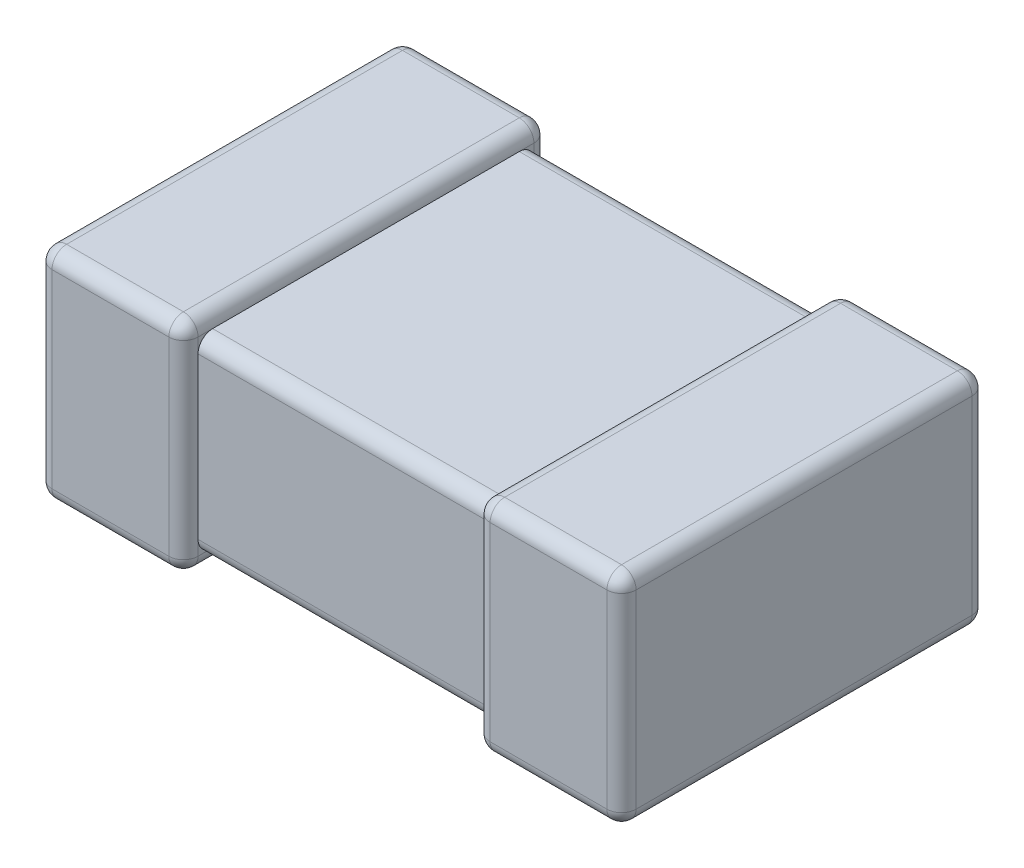
SolidWorks part; units mm, degrees
ref_plane "Front Plane" through (0, 0, 0) normal (0, 0, 1) x (1, 0, 0)
ref_plane "Top Plane" through (0, 0, 0) normal (0, 1, 0) x (1, 0, 0)
ref_plane "Right Plane" through (0, 0, 0) normal (1, 0, 0) x (0, 0, -1)
ref_plane "Plane4" through (0, 0.05, 0) normal (0, 1, 0) x (1, 0, 0)
sketch "Sketch1" plane through (0, 0.05, 0) normal (0, 1, 0) x (1, 0, 0)
  line L1 (-0.95, 0.575) -> (0.95, 0.575)
  line L2 (-0.95, 0.575) -> (-0.95, -0.575)
  line L3 (-0.95, -0.575) -> (0.95, -0.575)
  line L4 (0.95, 0.575) -> (0.95, -0.575)
  dimension "D1" = 1.9
  dimension "D2" = 0.95
  dimension "D3" = 1.15
  dimension "D4" = 0.575
extrude "Boss-Extrude1" add sketch "Sketch1" along normal blind 0.65
sketch "Sketch2" plane through (0, 0, 0) normal (0, 1, 0) x (1, 0, 0)
  line L0 (-0.95, 0.575) -> (-0.95, -0.575) construction
  line L1 (-1, 0.625) -> (-0.5, 0.625)
  line L2 (-1, 0.625) -> (-1, -0.625)
  line L3 (-1, -0.625) -> (-0.5, -0.625)
  line L4 (-0.5, 0.625) -> (-0.5, -0.625)
  line L5 (0.5, 0.625) -> (1, 0.625)
  line L6 (0.5, 0.625) -> (0.5, -0.625)
  line L7 (0.5, -0.625) -> (1, -0.625)
  line L8 (1, 0.625) -> (1, -0.625)
  line L9 (0.95, -0.575) -> (0.95, 0.575) construction
  line L10 (-0.95, -0.575) -> (0.95, -0.575) construction
  line L11 (0.95, 0.575) -> (-0.95, 0.575) construction
  dimension "D1" = 0.05
  dimension "D2" = 0.05
  dimension "D3" = 0.5
  dimension "D4" = 0.5
  dimension "D5" = 0.05
  dimension "D6" = 0.05
extrude "Boss-Extrude2" add sketch "Sketch2" along normal offset from surface (0.75 mm away) 0.05 separate body up to face at (0, 0.7, 0) offset beyond the face yes
fillet "Fillet1" radius 0.05 12 edges at (0.5, 0, 0) (0.75, 0, 0.625) (0.5, 0.375, 0.625) (1, 0, 0) (1, 0.375, 0.625) (0.5, 0.375, -0.625) (0.75, 0, -0.625) (1, 0.375, -0.625) (1, 0.75, 0) (0.75, 0.75, 0.625) (0.5, 0.75, 0) (0.75, 0.75, -0.625)
fillet "Fillet2" radius 0.05 12 edges at (-0.5, 0.375, -0.625) (-0.5, 0, 0) (-0.75, 0, -0.625) (-1, 0, 0) (-1, 0.375, -0.625) (-0.5, 0.375, 0.625) (-0.75, 0, 0.625) (-1, 0.375, 0.625) (-0.5, 0.75, 0) (-0.75, 0.75, 0.625) (-1, 0.75, 0) (-0.75, 0.75, -0.625)
fillet "Fillet3" radius 0.05 12 edges at (0.95, 0.05, 0) (-0.95, 0.05, 0) (0.95, 0.375, -0.575) (-0.95, 0.375, -0.575) (0, 0.05, -0.575) (-0.95, 0.375, 0.575) (0.95, 0.375, 0.575) (0, 0.05, 0.575) (0, 0.7, -0.575) (0.95, 0.7, 0) (0, 0.7, 0.575) (-0.95, 0.7, 0)
equation "\"D2@Sketch1\"=\"D1@Sketch1\"/2"
equation "\"D4@Sketch1\"=\"D3@Sketch1\"/2"
equation "\"D6@Sketch2\"=\"D5@Sketch2\""
